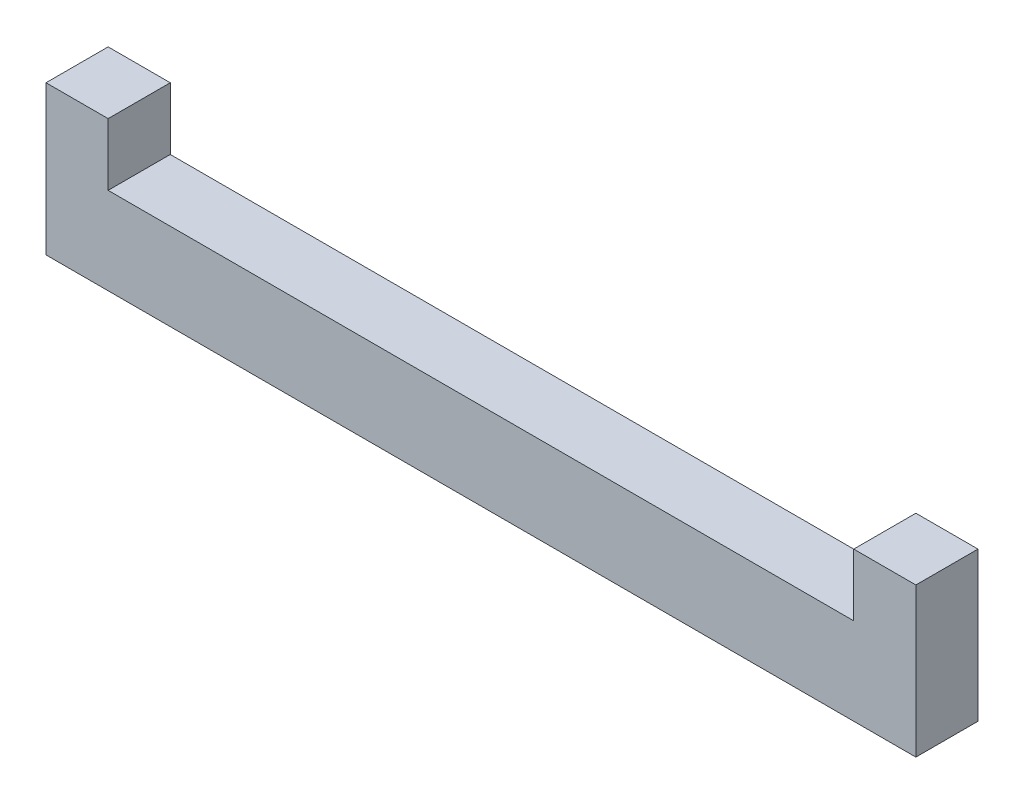
SolidWorks part; units mm, degrees
material "Balsa"
ref_plane "Plan de face" through (0, 0, 0) normal (0, 0, 1) x (1, 0, 0)
ref_plane "Plan de dessus" through (0, 0, 0) normal (0, 1, 0) x (1, 0, 0)
ref_plane "Plan de droite" through (0, 0, 0) normal (1, 0, 0) x (0, 0, -1)
sketch "Esquisse1" plane through (0, 0, 0) normal (0, 0, 1) x (1, 0, 0)
  line L0 (-133.9836, 222.4211) -> (-128.9836, 222.4211)
  line L1 (-128.9836, 222.4211) -> (-128.9836, 217.4211)
  line L2 (-128.9836, 217.4211) -> (-68.9836, 217.4211)
  line L3 (-133.9836, 222.4211) -> (-133.9836, 210.4211)
  line L4 (-133.9836, 210.4211) -> (-63.9836, 210.4211)
  line L5 (-98.9836, 222.4211) -> (-98.9836, 205.4211) construction
  line L6 (-63.9836, 222.4211) -> (-63.9836, 210.4211)
  line L7 (-68.9836, 222.4211) -> (-68.9836, 217.4211)
  line L8 (-63.9836, 222.4211) -> (-68.9836, 222.4211)
  dimension "D1" = 5
  dimension "D2" = 60
  dimension "D3" = 5
  dimension "D4" = 12
extrude "Boss.-Extru.1" add sketch "Esquisse1" against normal blind 5
